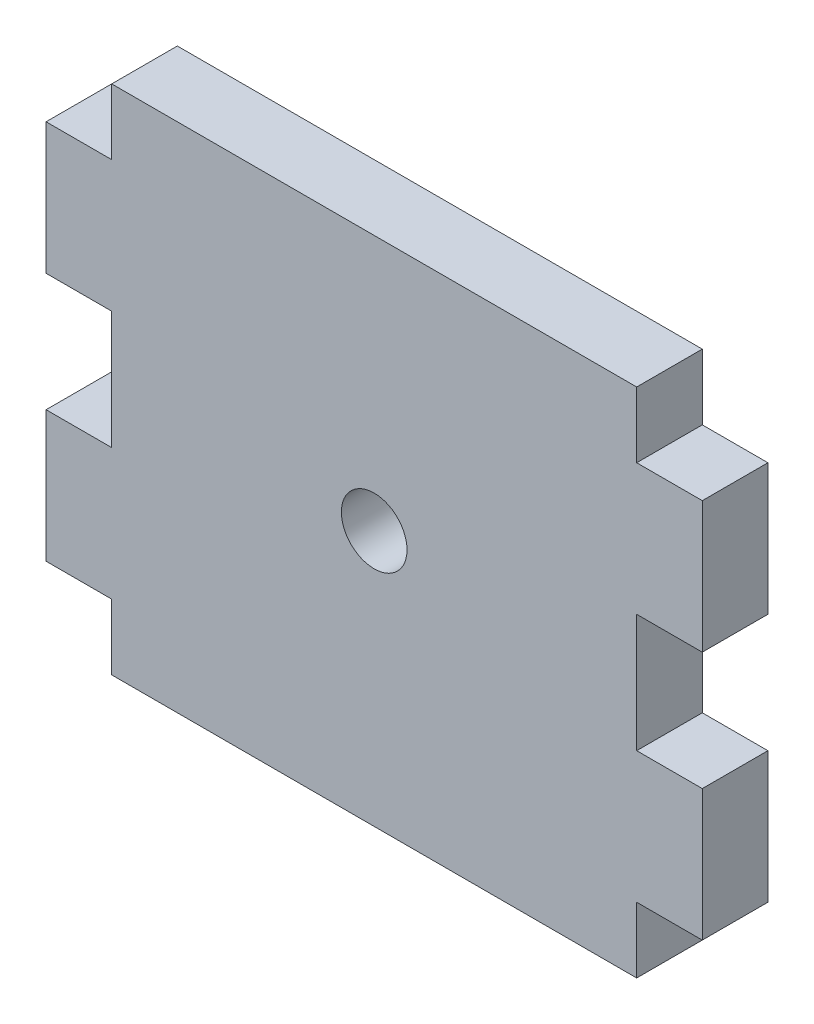
SolidWorks part; units mm, degrees
ref_plane "Front Plane" through (0, 0, 0) normal (0, 0, 1) x (1, 0, 0)
ref_plane "Top Plane" through (0, 0, 0) normal (0, 1, 0) x (1, 0, 0)
ref_plane "Right Plane" through (0, 0, 0) normal (1, 0, 0) x (0, 0, -1)
sketch "Sketch1" plane through (0, 0, 0) normal (0, 0, 1) x (1, 0, 0)
  line L0 (-25, 14.5) -> (-20, 14.5)
  line L1 (-20, -19.5) -> (20, -19.5)
  line L2 (-25, -14.5) -> (-25, -4.5)
  line L3 (-20, 19.5) -> (20, 19.5)
  line L4 (25, -14.5) -> (25, -4.5)
  line L5 (25, 14.5) -> (20, 14.5)
  line L7 (20, 4.5) -> (25, 4.5)
  line L8 (-20, 4.5) -> (-25, 4.5)
  line L9 (-25, -14.5) -> (-20, -14.5)
  line L10 (25, -4.5) -> (20, -4.5)
  line L11 (-20, -4.5) -> (-25, -4.5)
  line L12 (-20, 14.5) -> (-20, 19.5)
  line L13 (-20, 4.5) -> (-20, -4.5)
  line L14 (-25, 4.5) -> (-25, 14.5)
  line L15 (-20, -14.5) -> (-20, -19.5)
  line L17 (20, -14.5) -> (25, -14.5)
  line L18 (20, 14.5) -> (20, 19.5)
  line L19 (20, -14.5) -> (20, -19.5)
  line L20 (20, 4.5) -> (20, -4.5)
  line L21 (25, 4.5) -> (25, 14.5)
  circle A1 centre (0, 0) radius 2.5
  point P0 (0, 0)
  point P1 (0, 0)
  dimension "D3" = 5
  dimension "D5" = 5
  dimension "D1" = 10
  dimension "D2" = 10
  dimension "D4" = 5
  dimension "D6" = 10
  dimension "D7" = 5
  dimension "D8" = 10
  dimension "D9" = 5
  dimension "D10" = 5
  dimension "D11" = 5
  dimension "D12" = 9
  dimension "D13" = 9
  dimension "D14" = 40
  dimension "D15" = 40
extrude "Boss-Extrude1" add sketch "Sketch1" along normal blind 5
